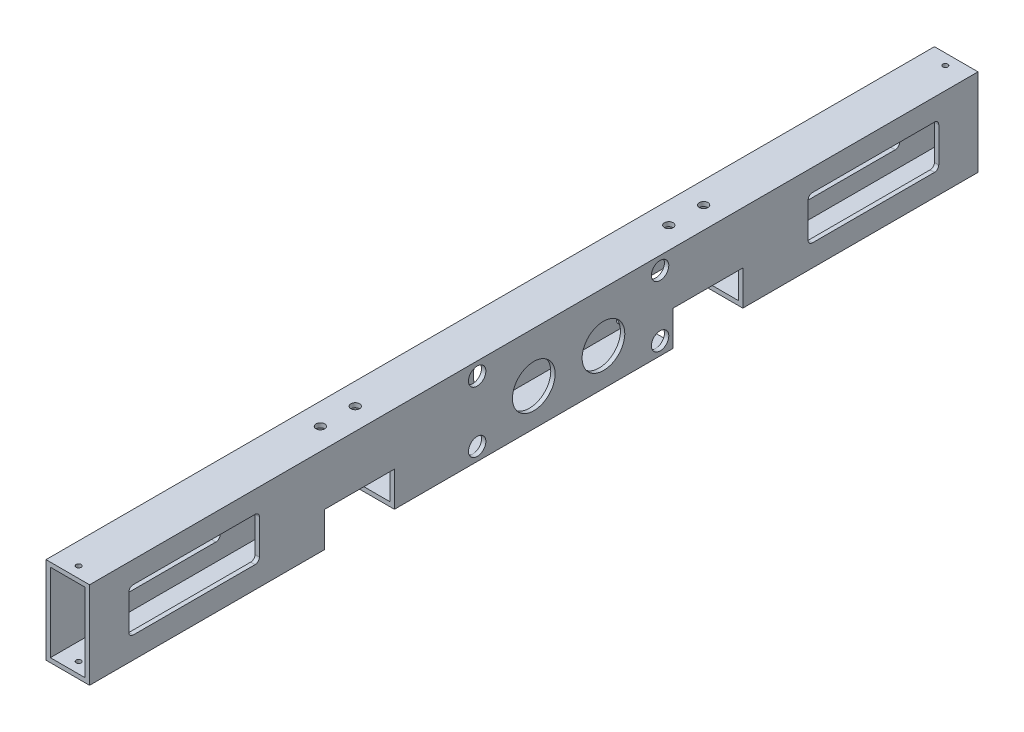
SolidWorks part; units mm, degrees
ref_plane "Front Plane" through (0, 0, 0) normal (0, 0, 1) x (1, 0, 0)
ref_plane "Top Plane" through (0, 0, 0) normal (0, 1, 0) x (1, 0, 0)
ref_plane "Right Plane" through (0, 0, 0) normal (1, 0, 0) x (0, 0, -1)
sketch "Sketch1" plane through (0, 0, 0) normal (0, 0, 1) x (1, 0, 0)
  line L1 (-12.1647, 2.5103) -> (19.5853, 2.5103)
  line L2 (-12.1647, 2.5103) -> (-12.1647, -60.9897)
  line L3 (-12.1647, -60.9897) -> (19.5853, -60.9897)
  line L4 (19.5853, 2.5103) -> (19.5853, -60.9897)
  line L5 (-8.9897, -0.6647) -> (16.4103, -0.6647)
  line L6 (-8.9897, -0.6647) -> (-8.9897, -57.8147)
  line L7 (-8.9897, -57.8147) -> (16.4103, -57.8147)
  line L8 (16.4103, -0.6647) -> (16.4103, -57.8147)
  dimension "D1" = 63.5
  dimension "D2" = 31.75
  dimension "D3" = 3.175
  dimension "D4" = 3.175
  dimension "D5" = 3.175
  dimension "D6" = 3.175
extrude "Boss-Extrude1" add sketch "Sketch1" along normal blind 647.7
sketch "Sketch3" plane through (-12.1647, 0, 0) normal (-1, 0, 0) x (0, 0, 1)
  line L0 (0, 2.5103) -> (0, -60.9897) construction
  line L1 (31.7754, -13.3647) -> (120.6754, -13.3647)
  line L2 (28.6004, -16.5397) -> (28.6004, -41.9397)
  line L3 (31.7754, -45.1147) -> (120.6754, -45.1147)
  line L4 (123.8504, -16.5397) -> (123.8504, -41.9397)
  line L5 (647.7, 2.5103) -> (0, 2.5103) construction
  line L6 (647.7, -60.9897) -> (0, -60.9897) construction
  line L7 (323.85, 2.5103) -> (323.85, -60.9897)
  line L8 (523.8496, -16.5397) -> (523.8496, -41.9397)
  line L9 (615.9246, -45.1147) -> (527.0246, -45.1147)
  line L10 (619.0996, -16.5397) -> (619.0996, -41.9397)
  line L11 (615.9246, -13.3647) -> (527.0246, -13.3647)
  line L12 (647.7, 2.5103) -> (647.7, -60.9897) construction
  line L13 (171.45, -60.9897) -> (222.25, -60.9897)
  line L14 (171.45, -60.9897) -> (171.45, -35.5897)
  line L15 (171.45, -35.5897) -> (222.25, -35.5897)
  line L16 (222.25, -60.9897) -> (222.25, -35.5897)
  line L17 (425.45, -60.9897) -> (476.25, -60.9897)
  line L18 (476.25, -60.9897) -> (476.25, -35.5897)
  line L19 (476.25, -35.5897) -> (425.45, -35.5897)
  line L20 (425.45, -60.9897) -> (425.45, -35.5897)
  arc A0 (28.6004, -41.9397) -> (31.7754, -45.1147) centre (31.7754, -41.9397) ccw
  arc A1 (120.6754, -45.1147) -> (123.8504, -41.9397) centre (120.6754, -41.9397) ccw
  arc A2 (120.6754, -13.3647) -> (123.8504, -16.5397) centre (120.6754, -16.5397) cw
  arc A3 (31.7754, -13.3647) -> (28.6004, -16.5397) centre (31.7754, -16.5397) ccw
  arc A4 (615.9246, -13.3647) -> (619.0996, -16.5397) centre (615.9246, -16.5397) cw
  arc A5 (527.0246, -13.3647) -> (523.8496, -16.5397) centre (527.0246, -16.5397) ccw
  arc A6 (527.0246, -45.1147) -> (523.8496, -41.9397) centre (527.0246, -41.9397) cw
  arc A7 (619.0996, -41.9397) -> (615.9246, -45.1147) centre (615.9246, -41.9397) cw
  line M7 (0, -60.9897) -> (647.7, -60.9897)
  dimension "D5" = 3.175
  dimension "D1" = 28.6004
  dimension "D2" = 15.875
  dimension "D3" = 15.875
  dimension "D4" = 95.25
  dimension "D6" = 25.4
  dimension "D7" = 50.8
  dimension "D8" = 171.45
  dimension "D9" = 50.8
  dimension "D10" = 25.4
  dimension "D11" = 171.45
extrude "Cut-Extrude1" cut sketch "Sketch3" against normal up to surface (31.75 mm away) contours L1 A3 L2 A0 L3 A1 L4 A2 | A7 L10 A4 L11 A5 L8 A6 L9 | L16 L15 L14 M7 | L20 L18 L19 M7 up to face at (19.5853, -29.2397, 323.85)
sketch "Sketch6" plane through (19.5853, 0, 0) normal (1, 0, 0) x (0, 0, -1)
  line L1 (-425.45, -60.9897) -> (-222.25, -60.9897) construction
  line L2 (-365.125, -7.0147) -> (-231.775, -7.0147) construction
  line L3 (-365.125, -7.0147) -> (-365.125, -51.4647) construction
  line L4 (-647.7, -60.9897) -> (-647.7, 2.5103) construction
  line L5 (-365.125, -51.4647) -> (-231.775, -51.4647) construction
  line L6 (-231.775, -7.0147) -> (-231.775, -51.4647) construction
  circle A0 centre (-323.85, -34.0022) radius 15.5575
  circle A1 centre (-273.05, -34.0022) radius 15.5575
  circle A2 centre (-365.125, -7.0147) radius 3.175
  circle A3 centre (-231.775, -7.0147) radius 3.175
  circle A4 centre (-365.125, -51.4647) radius 3.175
  circle A5 centre (-231.775, -51.4647) radius 3.175
  dimension "D1" = 31.115
  dimension "D4" = 50.8
  dimension "D6" = 17.4625
  dimension "D8" = 41.275
  dimension "D7" = 6.35
  dimension "D2" = 26.9875
  dimension "D3" = 323.85
  dimension "D5" = 26.9875
  dimension "D9" = 92.075
extrude "Cut-Extrude2" cut sketch "Sketch6" against normal up to surface (31.75 mm away) up to face at (-12.1647, -41.9397, 323.85)
sketch "Sketch7" plane through (19.5853, 0, 0) normal (1, 0, 0) x (0, 0, -1)
  circle A0 centre (-365.125, -7.0147) radius 6.35
  circle A1 centre (-365.125, -51.4647) radius 6.35
  circle A2 centre (-231.775, -51.4647) radius 6.35
  circle A3 centre (-231.775, -7.0147) radius 6.35
  dimension "D1" = 12.7
extrude "Cut-Extrude3" cut sketch "Sketch7" against normal up to next
sketch "Sketch8" plane through (0, 2.5103, 0) normal (0, 1, 0) x (1, 0, 0)
  line L0 (-12.1647, -323.85) -> (19.5853, -323.85) construction
  line L1 (-12.1647, -171.45) -> (19.5853, -171.45) construction
  line L2 (-12.1647, -171.45) -> (-12.1647, -222.25) construction
  line L3 (-12.1647, -222.25) -> (19.5853, -222.25) construction
  line L4 (19.5853, -171.45) -> (19.5853, -222.25) construction
  line L5 (3.7103, -476.25) -> (3.7103, -425.45) construction
  line L6 (-12.1647, -647.7) -> (-12.1647, 0) construction
  line L7 (19.5853, -647.7) -> (19.5853, 0) construction
  line L8 (19.5853, 0) -> (-12.1647, 0) construction
  line L9 (3.7103, -171.45) -> (3.7103, -222.25) construction
  line L10 (19.5853, -476.25) -> (19.5853, -425.45) construction
  line L11 (-12.1647, -425.45) -> (19.5853, -425.45) construction
  line L12 (-12.1647, -476.25) -> (-12.1647, -425.45) construction
  line L13 (-12.1647, -476.25) -> (19.5853, -476.25) construction
  circle A0 centre (3.7103, -184.15) radius 3.175
  circle A1 centre (3.7103, -209.55) radius 3.175
  circle A2 centre (3.7103, -438.15) radius 3.175
  circle A3 centre (3.7103, -463.55) radius 3.175
  dimension "D4" = 6.35
  dimension "D1" = 50.8
  dimension "D2" = 31.75
  dimension "D3" = 171.45
  dimension "D5" = 25.4
  dimension "D6" = 12.7
extrude "Cut-Extrude4" cut sketch "Sketch8" against normal through all
sketch "Sketch9" plane through (0, 2.5103, 0) normal (0, 1, 0) x (1, 0, 0)
  line L0 (19.5853, 0) -> (-12.1647, 0) construction
  line L1 (19.5853, -647.7) -> (-12.1647, -647.7) construction
  line L2 (-12.1647, -647.7) -> (-12.1647, 0) construction
  circle A0 centre (3.7103, -639.7625) radius 1.8415
  circle A1 centre (3.7103, -7.9375) radius 1.8415
  dimension "D1" = 7.9375
  dimension "D3" = 3.683
  dimension "D4" = 3.683
  dimension "D2" = 7.9375
  dimension "D5" = 15.875
  dimension "D6" = 15.875
extrude "Cut-Extrude5" cut sketch "Sketch9" against normal up to surface (63.5 mm away) up to face at (3.7103, -60.9897, 561.975)
